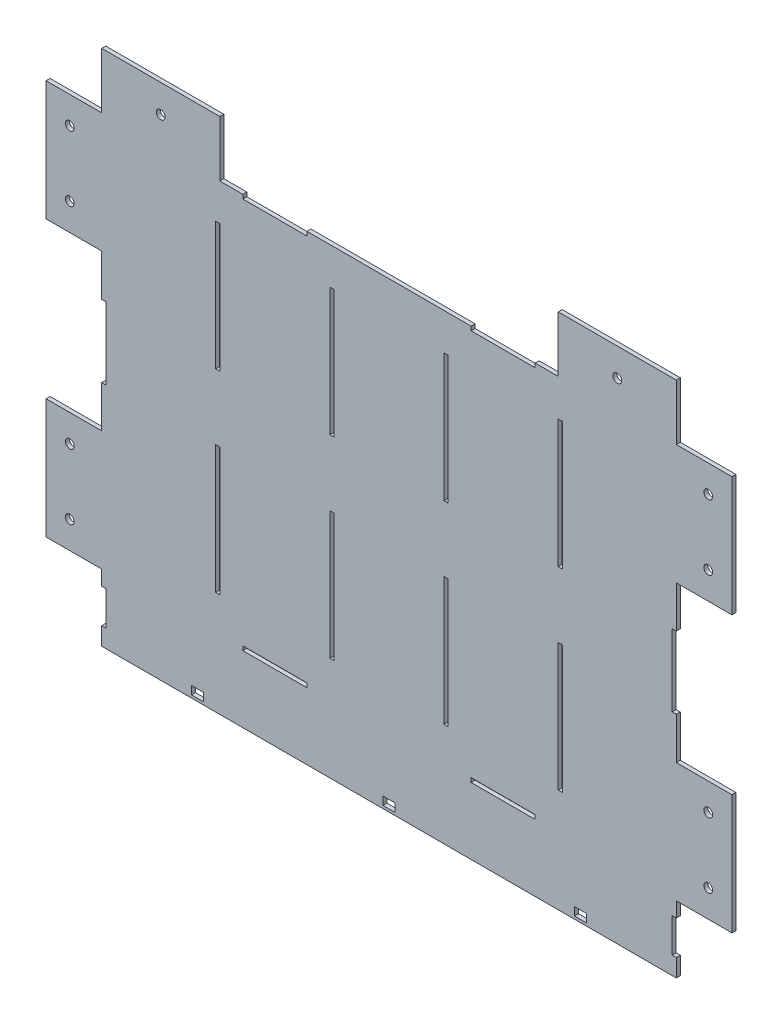
SolidWorks part; units mm, degrees
material "6061-T6 (SS)"
ref_plane "X-Y Datum" through (0, 0, 0) normal (0, 0, 1) x (1, 0, 0)
ref_plane "X-Z Datum" through (0, 0, 0) normal (0, 1, 0) x (1, 0, 0)
ref_plane "Y-Z Datum" through (0, 0, 0) normal (1, 0, 0) x (0, 0, -1)
sketch "Sketch1" plane through (0, 0, 0) normal (0, 0, 1) x (1, 0, 0)
  line L0 (-228.6115, 0) -> (228.6115, 0) construction
  line L1 (-228.6115, -157.216) -> (228.6115, -157.216)
  line L2 (-228.6115, -157.216) -> (-228.6115, 157.216)
  line L3 (-228.6115, 157.216) -> (228.6115, 157.216)
  line L4 (228.6115, -157.216) -> (228.6115, 157.216)
  line L5 (-228.6115, -157.216) -> (228.6115, 157.216) construction
  line L6 (-228.6115, 157.216) -> (228.6115, -157.216) construction
  line L8 (-228.6115, 0) -> (-134.6215, 0) construction
  line L9 (-225.4325, -154.041) -> (-225.4325, 154.041)
  line L10 (-224.4165, -153.025) -> (-138.8165, -153.025) construction
  line L15 (-224.4165, -153.025) -> (-224.4165, 153.025) construction
  line L16 (-224.4165, 153.025) -> (-138.8165, 153.025) construction
  line L17 (-138.8165, -153.025) -> (-138.8165, 153.025) construction
  line L18 (-224.4165, -153.025) -> (-138.8165, 153.025) construction
  line L19 (-224.4165, 153.025) -> (-138.8165, -153.025) construction
  line L20 (-225.4325, 154.041) -> (-137.8005, 154.041)
  line L21 (-137.8005, -154.041) -> (-137.8005, 154.041)
  line L22 (-225.4325, -154.041) -> (-137.8005, -154.041)
  line L26 (-134.6255, 154.041) -> (-46.9935, 154.041)
  line L27 (-133.6095, -153.025) -> (-48.0095, -153.025) construction
  line L28 (-133.6095, -153.025) -> (-133.6095, 153.025) construction
  line L29 (-133.6095, 153.025) -> (-48.0095, 153.025) construction
  line L30 (-48.0095, -153.025) -> (-48.0095, 153.025) construction
  line L31 (-133.6095, -153.025) -> (-48.0095, 153.025) construction
  line L32 (-133.6095, 153.025) -> (-48.0095, -153.025) construction
  line L33 (-46.9935, -154.041) -> (-46.9935, 154.041)
  line L34 (-134.6255, -154.041) -> (-46.9935, -154.041)
  line L35 (-134.6255, -154.041) -> (-134.6255, 154.041)
  line L36 (42.7975, -153.025) -> (42.7975, 153.025) construction
  line L37 (43.8135, -154.041) -> (43.8135, 154.041)
  line L38 (-42.8025, -153.025) -> (42.7975, 153.025) construction
  line L39 (-42.8025, 153.025) -> (42.7975, -153.025) construction
  line L40 (-42.8025, -153.025) -> (-42.8025, 153.025) construction
  line L41 (-43.8185, -154.041) -> (-43.8185, 154.041)
  line L42 (-42.8025, 153.025) -> (42.7975, 153.025) construction
  line L43 (-43.8185, 154.041) -> (43.8135, 154.041)
  line L44 (-42.8025, -153.025) -> (42.7975, -153.025) construction
  line L45 (-43.8185, -154.041) -> (43.8135, -154.041)
  line L46 (133.6045, -153.025) -> (133.6045, 153.025) construction
  line L47 (134.6205, -154.041) -> (134.6205, 154.041)
  line L48 (48.0045, -153.025) -> (133.6045, 153.025) construction
  line L49 (48.0045, 153.025) -> (133.6045, -153.025) construction
  line L50 (48.0045, -153.025) -> (48.0045, 153.025) construction
  line L51 (46.9885, -154.041) -> (46.9885, 154.041)
  line L52 (48.0045, 153.025) -> (133.6045, 153.025) construction
  line L53 (46.9885, 154.041) -> (134.6205, 154.041)
  line L54 (48.0045, -153.025) -> (133.6045, -153.025) construction
  line L55 (46.9885, -154.041) -> (134.6205, -154.041)
  line L56 (224.4115, -153.025) -> (224.4115, 153.025) construction
  line L57 (225.4275, -154.041) -> (225.4275, 154.041)
  line L58 (138.8115, -153.025) -> (224.4115, 153.025) construction
  line L59 (138.8115, 153.025) -> (224.4115, -153.025) construction
  line L60 (138.8115, -153.025) -> (138.8115, 153.025) construction
  line L61 (137.7955, -154.041) -> (137.7955, 154.041)
  line L62 (138.8115, 153.025) -> (224.4115, 153.025) construction
  line L63 (137.7955, 154.041) -> (225.4275, 154.041)
  line L64 (138.8115, -153.025) -> (224.4115, -153.025) construction
  line L65 (137.7955, -154.041) -> (225.4275, -154.041)
  line L67 (-228.6115, -157.216) -> (225.4365, -157.216)
  line L71 (-228.6115, -157.216) -> (228.6115, -157.216)
  line L74 (-225.4365, -157.216) -> (225.4365, -157.216)
  line L75 (-225.4365, -157.216) -> (-225.4365, -208.106)
  line L76 (-225.4365, -208.106) -> (225.4365, -208.106)
  line L77 (225.4365, -157.216) -> (225.4365, -208.106)
  line L79 (-228.6115, -157.216) -> (228.6115, -157.216)
  line L80 (-228.6115, -157.216) -> (-228.6115, -210.392)
  line L81 (-228.6115, -210.392) -> (228.6115, -210.392)
  line L82 (228.6115, -157.216) -> (228.6115, -210.392)
  point P0 (0, 0)
  point P10 (-181.6165, 0)
  point P22 (-90.8095, 0)
  dimension "D1" = 314.432
  dimension "D2" = 457.223
  dimension "D3" = 3.184
  dimension "D4" = 1.016
  dimension "D5" = 3.179
  dimension "D6" = 3.175
  dimension "D7" = 1.016
  dimension "D8" = 90.807
  dimension "D9" = 3.175
  dimension "D11" = 3.175
  dimension "D12" = 50.89
  dimension "D13" = 2.286
  dimension "D14" = 3.175
  dimension "D15" = 3.175
  dimension "D10" = 4
extrude "Boss-Extrude2" add sketch "Sketch1" along normal blind 3.175 contours L61 L65 L57 L63 | L51 L55 L47 L53 | L41 L45 L37 L43 | L35 L34 L33 L26 | L9 L22 L21 L20 | L1 L71 L4 L3 L2 L65 L61 L63 L57 L55 L51 L53 L47 L45 L41 L43 L37 L22 L9 L20 L21 L34 L35 L26 L33 | L77 L71 L75 L76 | L82 L1 L77 L76 L75 L80 L81
sketch "Sketch8" plane through (0, 0, 0) normal (0, 0, -1) x (-1, 0, 0)
  line L0 (-228.6115, -210.392) -> (-228.6115, 157.216) construction
  line L1 (-228.6115, 157.216) -> (-279.4115, 157.216)
  line L2 (-228.6115, 157.216) -> (-228.6115, 61.966)
  line L3 (-228.6115, 61.966) -> (-279.4115, 61.966)
  line L4 (-279.4115, 157.216) -> (-279.4115, 61.966)
  line L5 (-228.6115, -157.216) -> (-279.4115, -157.216)
  line L6 (-228.6115, -157.216) -> (-228.6115, -61.966)
  line L7 (-228.6115, -61.966) -> (-279.4115, -61.966)
  line L8 (-279.4115, -157.216) -> (-279.4115, -61.966)
  line L9 (-254.0115, 83.591) -> (-254.0115, 135.591)
  line L10 (-254.0115, -83.591) -> (-254.0115, -135.591) construction
  line L11 (-279.4115, 109.591) -> (-228.6115, 109.591) construction
  line L13 (-272.8865, 157.216) -> (-272.8865, 61.966)
  line L15 (-228.6115, -109.591) -> (-279.4115, -109.591) construction
  line L16 (-181.6215, 201.666) -> (-181.6215, 157.216) construction
  line L17 (-228.6115, 157.216) -> (-134.6315, 157.216)
  line L18 (-228.6115, 157.216) -> (-228.6115, 201.666)
  line L19 (-228.6115, 201.666) -> (-134.6315, 201.666)
  line L20 (-134.6315, 157.216) -> (-134.6315, 201.666)
  line L22 (228.6115, 157.216) -> (-228.6115, 157.216) construction
  line L23 (-272.8865, -61.966) -> (-272.8865, -157.216)
  circle A3 centre (-254.0115, -83.591) radius 3
  circle A4 centre (-254.0115, -135.591) radius 3
  circle A5 centre (-181.6215, 179.441) radius 3
  circle A6 centre (-254.0115, 135.591) radius 3
  circle A7 centre (-254.0115, 83.591) radius 3
  point P13 (-254.0115, -109.591)
  point P19 (-254.0115, 109.591)
  point P21 (-257.0115, 135.591)
  point P45 (-254.0115, -138.591)
  point P46 (-254.0115, -157.216)
  dimension "D1" = 95.25
  dimension "D2" = 52
  dimension "D4" = 52
  dimension "D5" = 6
  dimension "D7" = 93.98
  dimension "D8" = 123.932
  dimension "D9" = 25.4
  dimension "D3" = 6
  dimension "D11" = 6
  dimension "D6" = 22.225
  dimension "D10" = 15.875
extrude "Boss-Extrude3" add sketch "Sketch8" against normal blind 3.175
mirror "Mirror7" about plane through (0, 0, 0) normal (1, 0, 0) of "Boss-Extrude3"
hole_wizard "M6 Clearance Hole1" positions "Sketch11" profile "Sketch10" hole size "M6" standard "ANSI Metric" end condition through all
sketch "Sketch11" plane through (0, 0, 0) normal (0, 0, -1) x (-1, 0, 0)
  point P0 (-254.0115, -135.591)
  point P3 (-254.0115, -83.591)
  point P6 (-254.0115, 83.591)
  point P9 (-254.0115, 135.591)
  point P12 (-181.6215, 179.441)
sketch "Sketch10" plane through (254.0115, -135.591, 0) normal (1, 0, 0) x (0, 1, 0)
  line L0 (0, 0) -> (0, 3.175)
  line L1 (0, 3.175) -> (3.5, 3.175)
  line L2 (3.5, 3.175) -> (3.5, 0)
  line L5 (3.5, 0) -> (0, 0)
  line L11 (0, -6.35) -> (0, 107.95) construction
  dimension "Thru Hole Dia." = 7
  dimension "Thru Hole Depth" = 3.175
mirror "Mirror8" about plane through (0, 0, 0) normal (1, 0, 0) of "M6 Clearance Hole1"
sketch "Sketch12" plane through (0, 0, 0) normal (0, 0, -1) x (-1, 0, 0)
  line L0 (228.6115, -157.216) -> (-228.6115, -157.216) construction
  line L1 (228.6115, -157.216) -> (228.6115, 157.216) construction
  line L2 (228.6115, 157.216) -> (-228.6115, 157.216) construction
  line L3 (-228.6115, -157.216) -> (-228.6115, 157.216) construction
  line L4 (228.6115, -157.216) -> (-228.6115, -157.216) construction
  line L5 (228.6115, -157.216) -> (-228.6115, -157.216) construction
  line L6 (228.6115, -157.216) -> (228.6115, -210.392) construction
  line L7 (228.6115, -210.392) -> (-228.6115, -210.392) construction
  line L8 (-228.6115, -157.216) -> (-228.6115, -210.392) construction
  line L9 (228.6115, -157.216) -> (-225.4365, -157.216) construction
  line L10 (225.4325, -154.041) -> (225.4325, 154.041) construction
  line L11 (225.4325, 154.041) -> (137.8005, 154.041) construction
  line L12 (137.8005, -154.041) -> (137.8005, 154.041) construction
  line L13 (225.4325, -154.041) -> (137.8005, -154.041) construction
  line L14 (-43.8135, -154.041) -> (-43.8135, 154.041) construction
  line L15 (43.8185, 154.041) -> (-43.8135, 154.041) construction
  line L16 (43.8185, -154.041) -> (43.8185, 154.041) construction
  line L17 (43.8185, -154.041) -> (-43.8135, -154.041) construction
  line L18 (134.6255, -154.041) -> (46.9935, -154.041) construction
  line L19 (46.9935, -154.041) -> (46.9935, 154.041) construction
  line L20 (134.6255, 154.041) -> (46.9935, 154.041) construction
  line L21 (134.6255, -154.041) -> (134.6255, 154.041) construction
  line L22 (225.4365, -157.216) -> (-225.4365, -157.216) construction
  line L23 (225.4365, -157.216) -> (225.4365, -208.106) construction
  line L24 (225.4365, -208.106) -> (-225.4365, -208.106) construction
  line L25 (-225.4365, -157.216) -> (-225.4365, -208.106) construction
  line L26 (-225.4275, -154.041) -> (-225.4275, 154.041) construction
  line L27 (-137.7955, 154.041) -> (-225.4275, 154.041) construction
  line L28 (-137.7955, -154.041) -> (-137.7955, 154.041) construction
  line L29 (-137.7955, -154.041) -> (-225.4275, -154.041) construction
  line L30 (-134.6205, -154.041) -> (-134.6205, 154.041) construction
  line L31 (-46.9885, 154.041) -> (-134.6205, 154.041) construction
  line L32 (-46.9885, -154.041) -> (-46.9885, 154.041) construction
  line L33 (-46.9885, -154.041) -> (-134.6205, -154.041) construction
  line L34 (228.6115, -157.216) -> (-228.6115, -157.216) construction
  line L35 (228.6115, -157.216) -> (228.6115, 157.216) construction
  line L36 (228.6115, 157.216) -> (-228.6115, 157.216) construction
  line L37 (-228.6115, -157.216) -> (-228.6115, 157.216) construction
  line L38 (228.6115, -157.216) -> (-228.6115, -157.216) construction
  line L39 (228.6115, -157.216) -> (-228.6115, -157.216) construction
  line L40 (228.6115, -157.216) -> (228.6115, -210.392) construction
  line L41 (228.6115, -210.392) -> (-228.6115, -210.392)
  line L42 (-228.6115, -157.216) -> (-228.6115, -210.392)
  line L43 (228.6115, -157.216) -> (-225.4365, -157.216) construction
  line L44 (225.4325, -154.041) -> (225.4325, 154.041) construction
  line L45 (225.4325, 154.041) -> (137.8005, 154.041) construction
  line L46 (137.8005, -154.041) -> (137.8005, 154.041) construction
  line L47 (225.4325, -154.041) -> (137.8005, -154.041) construction
  line L48 (-43.8135, -154.041) -> (-43.8135, 154.041) construction
  line L49 (43.8185, 154.041) -> (-43.8135, 154.041) construction
  line L50 (43.8185, -154.041) -> (43.8185, 154.041) construction
  line L51 (43.8185, -154.041) -> (-43.8135, -154.041) construction
  line L52 (134.6255, -154.041) -> (46.9935, -154.041) construction
  line L53 (46.9935, -154.041) -> (46.9935, 154.041) construction
  line L54 (134.6255, 154.041) -> (46.9935, 154.041) construction
  line L55 (134.6255, -154.041) -> (134.6255, 154.041) construction
  line L56 (225.4365, -157.216) -> (-225.4365, -157.216) construction
  line L57 (225.4365, -157.216) -> (225.4365, -208.106) construction
  line L58 (225.4365, -208.106) -> (-225.4365, -208.106) construction
  line L59 (-225.4365, -157.216) -> (-225.4365, -208.106) construction
  line L60 (-225.4275, -154.041) -> (-225.4275, 154.041) construction
  line L61 (-137.7955, 154.041) -> (-225.4275, 154.041) construction
  line L62 (-137.7955, -154.041) -> (-137.7955, 154.041) construction
  line L63 (-137.7955, -154.041) -> (-225.4275, -154.041) construction
  line L64 (-134.6205, -154.041) -> (-134.6205, 154.041) construction
  line L65 (-46.9885, 154.041) -> (-134.6205, 154.041) construction
  line L66 (-46.9885, -154.041) -> (-46.9885, 154.041) construction
  line L67 (-46.9885, -154.041) -> (-134.6205, -154.041) construction
  line L68 (-228.6115, 0) -> (-225.4275, 0) construction
  line L69 (-90.8045, 154.041) -> (-90.8045, 157.216) construction
  line L70 (-90.8045, -154.041) -> (-90.8045, -157.216) construction
  line L71 (225.4325, 0) -> (228.6115, 0) construction
  line L72 (90.8095, -154.041) -> (90.8095, -157.216) construction
  line L73 (90.8095, 154.041) -> (90.8095, 157.216) construction
  line L74 (134.6255, 0) -> (137.8005, 0)
  line L75 (43.8185, 0) -> (46.9935, 0)
  line L76 (-46.9885, 0) -> (-43.8135, 0)
  line L77 (-137.7955, 0) -> (-134.6205, 0)
  line L78 (-225.4365, -182.661) -> (-228.6115, -182.661) construction
  line L79 (-228.6115, 28.575) -> (-225.4275, 28.575)
  line L80 (-228.6115, 28.575) -> (-228.6115, -28.575)
  line L81 (-228.6115, -28.575) -> (-225.4275, -28.575)
  line L82 (-225.4275, 28.575) -> (-225.4275, -28.575)
  line L83 (-228.6115, 28.575) -> (-225.4275, -28.575) construction
  line L84 (-228.6115, -28.575) -> (-225.4275, 28.575) construction
  line L85 (225.4325, 28.575) -> (228.6115, 28.575)
  line L86 (225.4325, 28.575) -> (225.4325, -28.575)
  line L87 (225.4325, -28.575) -> (228.6115, -28.575)
  line L88 (228.6115, 28.575) -> (228.6115, -28.575)
  line L89 (225.4325, 28.575) -> (228.6115, -28.575) construction
  line L90 (225.4325, -28.575) -> (228.6115, 28.575) construction
  line L91 (-116.2045, 157.216) -> (-65.4045, 157.216)
  line L92 (-116.2045, 157.216) -> (-116.2045, 154.041)
  line L93 (-116.2045, 154.041) -> (-65.4045, 154.041)
  line L94 (-65.4045, 157.216) -> (-65.4045, 154.041)
  line L95 (-116.2045, 157.216) -> (-65.4045, 154.041) construction
  line L96 (-116.2045, 154.041) -> (-65.4045, 157.216) construction
  line L97 (65.4095, 157.216) -> (116.2095, 157.216)
  line L98 (65.4095, 157.216) -> (65.4095, 154.041)
  line L99 (65.4095, 154.041) -> (116.2095, 154.041)
  line L100 (116.2095, 157.216) -> (116.2095, 154.041)
  line L101 (65.4095, 157.216) -> (116.2095, 154.041) construction
  line L102 (65.4095, 154.041) -> (116.2095, 157.216) construction
  line L103 (-116.2045, -154.041) -> (-65.4045, -154.041)
  line L104 (-116.2045, -154.041) -> (-116.2045, -157.216)
  line L105 (-116.2045, -157.216) -> (-65.4045, -157.216)
  line L106 (-65.4045, -154.041) -> (-65.4045, -157.216)
  line L107 (-116.2045, -154.041) -> (-65.4045, -157.216) construction
  line L108 (-116.2045, -157.216) -> (-65.4045, -154.041) construction
  line L109 (65.4095, -154.041) -> (116.2095, -154.041)
  line L110 (65.4095, -154.041) -> (65.4095, -157.216)
  line L111 (65.4095, -157.216) -> (116.2095, -157.216)
  line L112 (116.2095, -154.041) -> (116.2095, -157.216)
  line L113 (65.4095, -154.041) -> (116.2095, -157.216) construction
  line L114 (65.4095, -157.216) -> (116.2095, -154.041) construction
  line L115 (225.4365, -182.661) -> (228.6115, -182.661) construction
  line L116 (-136.208, 0) -> (-136.208, 154.041) construction
  line L117 (-228.6115, -169.1673) -> (-225.4365, -169.1673)
  line L118 (-228.6115, -169.1673) -> (-228.6115, -196.1548)
  line L119 (-228.6115, -196.1548) -> (-225.4365, -196.1548)
  line L120 (-225.4365, -169.1673) -> (-225.4365, -196.1548)
  line L121 (-228.6115, -169.1673) -> (-225.4365, -196.1548) construction
  line L122 (-228.6115, -196.1548) -> (-225.4365, -169.1673) construction
  line L123 (225.4365, -169.1673) -> (228.6115, -169.1673)
  line L124 (225.4365, -169.1673) -> (225.4365, -196.1548)
  line L125 (225.4365, -196.1548) -> (228.6115, -196.1548)
  line L126 (228.6115, -169.1673) -> (228.6115, -196.1548)
  line L127 (225.4365, -169.1673) -> (228.6115, -196.1548) construction
  line L128 (225.4365, -196.1548) -> (228.6115, -169.1673) construction
  line L129 (-136.208, 0) -> (-136.208, -154.041) construction
  line L130 (-228.6877, 28.6512) -> (-225.3513, 28.6512)
  line L131 (-137.7955, 127.8205) -> (-134.6205, 127.8205)
  line L132 (-137.7955, 127.8205) -> (-137.7955, 26.2205)
  line L133 (-137.7955, 26.2205) -> (-134.6205, 26.2205)
  line L134 (-134.6205, 127.8205) -> (-134.6205, 26.2205)
  line L135 (-137.7955, 127.8205) -> (-134.6205, 26.2205) construction
  line L136 (-137.7955, 26.2205) -> (-134.6205, 127.8205) construction
  line L137 (-137.7955, -26.2205) -> (-134.6205, -26.2205)
  line L138 (-137.7955, -26.2205) -> (-137.7955, -127.8205)
  line L139 (-137.7955, -127.8205) -> (-134.6205, -127.8205)
  line L140 (-134.6205, -26.2205) -> (-134.6205, -127.8205)
  line L141 (-137.7955, -26.2205) -> (-134.6205, -127.8205) construction
  line L142 (-137.7955, -127.8205) -> (-134.6205, -26.2205) construction
  line L143 (-225.3513, 28.6512) -> (-225.3513, -28.6512)
  line L144 (-228.6877, -28.6512) -> (-225.3513, -28.6512)
  line L145 (-228.6877, 28.6512) -> (-228.6877, -28.6512)
  line L146 (-225.3603, -169.0911) -> (-225.3603, -196.231)
  line L147 (-228.6877, -196.231) -> (-225.3603, -196.231)
  line L148 (-228.6877, -169.0911) -> (-228.6877, -196.231)
  line L149 (-228.6877, -169.0911) -> (-225.3603, -169.0911)
  line L150 (-116.2807, -153.9648) -> (-116.2807, -157.2922)
  line L151 (-116.2807, -157.2922) -> (-65.3283, -157.2922)
  line L152 (-65.3283, -153.9648) -> (-65.3283, -157.2922)
  line L153 (-116.2807, -153.9648) -> (-65.3283, -153.9648)
  line L154 (65.3333, -153.9648) -> (65.3333, -157.2922)
  line L155 (65.3333, -157.2922) -> (116.2857, -157.2922)
  line L156 (116.2857, -153.9648) -> (116.2857, -157.2922)
  line L157 (65.3333, -153.9648) -> (116.2857, -153.9648)
  line L158 (225.3603, -169.0911) -> (228.6877, -169.0911)
  line L159 (228.6877, -169.0911) -> (228.6877, -196.231)
  line L160 (225.3603, -196.231) -> (228.6877, -196.231)
  line L161 (225.3603, -169.0911) -> (225.3603, -196.231)
  line L162 (-116.2807, 157.2922) -> (-116.2807, 153.9648)
  line L163 (-116.2807, 153.9648) -> (-65.3283, 153.9648)
  line L164 (-65.3283, 157.2922) -> (-65.3283, 153.9648)
  line L165 (-116.2807, 157.2922) -> (-65.3283, 157.2922)
  line L166 (65.3333, 157.2922) -> (65.3333, 153.9648)
  line L167 (65.3333, 153.9648) -> (116.2857, 153.9648)
  line L168 (116.2857, 157.2922) -> (116.2857, 153.9648)
  line L169 (65.3333, 157.2922) -> (116.2857, 157.2922)
  line L170 (225.3563, 28.6512) -> (228.6877, 28.6512)
  line L171 (228.6877, 28.6512) -> (228.6877, -28.6512)
  line L172 (225.3563, -28.6512) -> (228.6877, -28.6512)
  line L173 (225.3563, 28.6512) -> (225.3563, -28.6512)
  point P50 (-227.0195, 0)
  point P55 (227.022, 0)
  point P60 (-90.8045, 155.6285)
  point P65 (90.8095, 155.6285)
  point P70 (-90.8045, -155.6285)
  point P75 (90.8095, -155.6285)
  point P84 (-227.024, -182.661)
  point P89 (227.024, -182.661)
  point P96 (-136.208, -77.0205)
  point P98 (-136.208, 77.0205)
  line M27 (228.6115, -210.392) -> (228.6115, -157.216)
  line M31 (228.6115, -61.966) -> (228.6115, 61.966)
  line M38 (134.6315, 157.216) -> (-134.6315, 157.216)
  line M45 (-228.6115, 61.966) -> (-228.6115, -61.966)
  line M49 (-228.6115, -157.216) -> (-228.6115, -210.392)
  dimension "D1" = 57.15
  dimension "D2" = 50.8
  dimension "D3" = 26.9875
  dimension "D4" = 101.6
  dimension "D5" = 0.0762
  dimension "D6" = 0.0762
extrude "Cut-Extrude3" cut sketch "Sketch12" against normal through all contours L82 L79 L81 M45 | L144 L143 L130 L79 L82 L81 M45 | L120 L117 L42 L119 | L149 L42 L117 L120 L119 L147 L146 M49 | L106 L103 L104 L105 | L153 L150 L151 L152 L103 L106 L105 L104 | L112 L109 L110 L111 | L157 L154 L155 L156 L109 L112 L111 L110 | L124 L125 L123 M27 | L158 L161 L160 L125 L124 L123 M27 | L86 L87 L85 M31 | L170 L173 L172 L87 L86 L85 M31 | L100 L98 L99 M38 | L168 L100 L99 L98 L166 L167 M38 | L94 L92 L93 M38 | L164 L94 L93 L92 L162 L163 M38
sketch "Sketch14" plane through (0, 0, 0) normal (0, 0, -1) x (-1, 0, 0)
  line L0 (228.6115, -210.392) -> (-228.6115, -210.392) construction
  line L1 (-228.6115, -157.216) -> (-228.6115, -210.392) construction
  line L2 (-137.7955, 0) -> (-134.6205, 0) construction
  line L3 (-46.9885, 0) -> (-43.8135, 0) construction
  line L4 (228.6115, 28.575) -> (225.4325, 28.575)
  line L5 (228.6115, -28.575) -> (228.6115, 28.575)
  line L6 (225.4325, -28.575) -> (228.6115, -28.575)
  line L7 (225.4325, 28.575) -> (225.4325, -28.575)
  line L8 (228.6115, 28.575) -> (225.4325, 28.575)
  line L9 (228.6115, -28.575) -> (228.6115, 28.575)
  line L10 (225.4325, -28.575) -> (228.6115, -28.575)
  line L11 (225.4325, 28.575) -> (225.4325, -28.575)
  line L12 (-225.4275, 28.575) -> (-228.6115, 28.575)
  line L13 (-225.4275, -28.575) -> (-225.4275, 28.575)
  line L14 (-228.6115, -28.575) -> (-225.4275, -28.575)
  line L15 (-228.6115, 28.575) -> (-228.6115, -28.575)
  line L16 (-225.4275, 28.575) -> (-228.6115, 28.575)
  line L17 (-225.4275, -28.575) -> (-225.4275, 28.575)
  line L18 (-228.6115, -28.575) -> (-225.4275, -28.575)
  line L19 (-228.6115, 28.575) -> (-228.6115, -28.575)
  line L20 (116.2095, -154.041) -> (65.4095, -154.041)
  line L21 (116.2095, -157.216) -> (116.2095, -154.041)
  line L22 (65.4095, -157.216) -> (116.2095, -157.216)
  line L23 (65.4095, -154.041) -> (65.4095, -157.216)
  line L24 (116.2095, -154.041) -> (65.4095, -154.041)
  line L25 (116.2095, -157.216) -> (116.2095, -154.041)
  line L26 (65.4095, -157.216) -> (116.2095, -157.216)
  line L27 (65.4095, -154.041) -> (65.4095, -157.216)
  line L28 (-65.4045, -154.041) -> (-116.2045, -154.041)
  line L29 (-65.4045, -157.216) -> (-65.4045, -154.041)
  line L30 (-116.2045, -157.216) -> (-65.4045, -157.216)
  line L31 (-116.2045, -154.041) -> (-116.2045, -157.216)
  line L32 (-65.4045, -154.041) -> (-116.2045, -154.041)
  line L33 (-65.4045, -157.216) -> (-65.4045, -154.041)
  line L34 (-116.2045, -157.216) -> (-65.4045, -157.216)
  line L35 (-116.2045, -154.041) -> (-116.2045, -157.216)
  line L36 (116.2095, 157.216) -> (65.4095, 157.216)
  line L37 (116.2095, 154.041) -> (116.2095, 157.216)
  line L38 (65.4095, 154.041) -> (116.2095, 154.041)
  line L39 (65.4095, 157.216) -> (65.4095, 154.041)
  line L40 (116.2095, 157.216) -> (65.4095, 157.216)
  line L41 (116.2095, 154.041) -> (116.2095, 157.216)
  line L42 (65.4095, 154.041) -> (116.2095, 154.041)
  line L43 (65.4095, 157.216) -> (65.4095, 154.041)
  line L44 (-65.4045, 157.216) -> (-116.2045, 157.216)
  line L45 (-116.2045, 157.216) -> (-116.2045, 154.041)
  line L46 (-116.2045, 154.041) -> (-65.4045, 154.041)
  line L47 (-65.4045, 154.041) -> (-65.4045, 157.216)
  line L48 (-65.4045, 157.216) -> (-116.2045, 157.216)
  line L49 (-116.2045, 157.216) -> (-116.2045, 154.041)
  line L50 (-116.2045, 154.041) -> (-65.4045, 154.041)
  line L51 (-65.4045, 154.041) -> (-65.4045, 157.216)
  line L52 (228.6115, -169.1673) -> (225.4365, -169.1673)
  line L53 (228.6115, -196.1548) -> (228.6115, -169.1673)
  line L54 (225.4365, -196.1548) -> (228.6115, -196.1548)
  line L55 (225.4365, -169.1673) -> (225.4365, -196.1548)
  line L56 (228.6115, -169.1673) -> (225.4365, -169.1673)
  line L57 (228.6115, -196.1548) -> (228.6115, -169.1673)
  line L58 (225.4365, -196.1548) -> (228.6115, -196.1548)
  line L59 (225.4365, -169.1673) -> (225.4365, -196.1548)
  line L60 (-225.4365, -169.1673) -> (-228.6115, -169.1673)
  line L61 (-225.4365, -196.1548) -> (-225.4365, -169.1673)
  line L62 (-228.6115, -196.1548) -> (-225.4365, -196.1548)
  line L63 (-228.6115, -169.1673) -> (-228.6115, -196.1548)
  line L64 (-225.4365, -169.1673) -> (-228.6115, -169.1673)
  line L65 (-225.4365, -196.1548) -> (-225.4365, -169.1673)
  line L66 (-228.6115, -196.1548) -> (-225.4365, -196.1548)
  line L67 (-228.6115, -169.1673) -> (-228.6115, -196.1548)
  line L68 (-134.6205, -26.2205) -> (-137.7955, -26.2205)
  line L69 (-134.6205, -127.8205) -> (-134.6205, -26.2205)
  line L70 (-137.7955, -127.8205) -> (-134.6205, -127.8205)
  line L71 (-137.7955, -26.2205) -> (-137.7955, -127.8205)
  line L72 (-134.6205, -26.2205) -> (-137.7955, -26.2205)
  line L73 (-134.6205, -127.8205) -> (-134.6205, -26.2205)
  line L74 (-137.7955, -127.8205) -> (-134.6205, -127.8205)
  line L75 (-137.7955, -26.2205) -> (-137.7955, -127.8205)
  line L76 (-134.6205, 127.8205) -> (-137.7955, 127.8205)
  line L77 (-134.6205, 26.2205) -> (-134.6205, 127.8205)
  line L78 (-137.7955, 26.2205) -> (-134.6205, 26.2205)
  line L79 (-137.7955, 127.8205) -> (-137.7955, 26.2205)
  line L80 (-134.6205, 127.8205) -> (-137.7955, 127.8205)
  line L81 (-134.6205, 26.2205) -> (-134.6205, 127.8205)
  line L82 (-137.7955, 26.2205) -> (-134.6205, 26.2205)
  line L83 (-137.7955, 127.8205) -> (-137.7955, 26.2205)
  line L84 (65.3333, -153.9648) -> (65.3333, -157.2922)
  line L85 (65.3333, -157.2922) -> (116.2857, -157.2922)
  line L86 (116.2857, -157.2922) -> (116.2857, -153.9648)
  line L87 (116.2857, -153.9648) -> (65.3333, -153.9648)
  line L88 (65.3333, -153.9648) -> (65.3333, -157.2922)
  line L89 (65.3333, -157.2922) -> (116.2857, -157.2922)
  line L90 (116.2857, -157.2922) -> (116.2857, -153.9648)
  line L91 (116.2857, -153.9648) -> (65.3333, -153.9648)
  line L92 (-116.2807, -153.9648) -> (-116.2807, -157.2922)
  line L93 (-116.2807, -157.2922) -> (-65.3283, -157.2922)
  line L94 (-65.3283, -157.2922) -> (-65.3283, -153.9648)
  line L95 (-65.3283, -153.9648) -> (-116.2807, -153.9648)
  line L96 (-116.2807, -153.9648) -> (-116.2807, -157.2922)
  line L97 (-116.2807, -157.2922) -> (-65.3283, -157.2922)
  line L98 (-65.3283, -157.2922) -> (-65.3283, -153.9648)
  line L99 (-65.3283, -153.9648) -> (-116.2807, -153.9648)
  line L100 (-225.3603, -196.231) -> (-225.3603, -169.0911)
  line L101 (-228.6877, -196.231) -> (-225.3603, -196.231)
  line L102 (-228.6877, -169.0911) -> (-228.6877, -196.231)
  line L103 (-225.3603, -169.0911) -> (-228.6877, -169.0911)
  line L104 (-225.3603, -196.231) -> (-225.3603, -169.0911)
  line L105 (-228.6877, -196.231) -> (-225.3603, -196.231)
  line L106 (-228.6877, -169.0911) -> (-228.6877, -196.231)
  line L107 (-225.3603, -169.0911) -> (-228.6877, -169.0911)
  line L108 (-228.6877, -28.6512) -> (-225.3513, -28.6512)
  line L109 (-228.6877, 28.6512) -> (-228.6877, -28.6512)
  line L110 (-225.3513, 28.6512) -> (-228.6877, 28.6512)
  line L111 (-225.3513, -28.6512) -> (-225.3513, 28.6512)
  line L112 (-228.6877, -28.6512) -> (-225.3513, -28.6512)
  line L113 (-228.6877, 28.6512) -> (-228.6877, -28.6512)
  line L114 (-225.3513, 28.6512) -> (-228.6877, 28.6512)
  line L115 (-225.3513, -28.6512) -> (-225.3513, 28.6512)
  line L116 (228.6877, 28.6512) -> (225.3563, 28.6512)
  line L117 (228.6877, -28.6512) -> (228.6877, 28.6512)
  line L118 (225.3563, -28.6512) -> (228.6877, -28.6512)
  line L119 (225.3563, 28.6512) -> (225.3563, -28.6512)
  line L120 (228.6877, 28.6512) -> (225.3563, 28.6512)
  line L121 (228.6877, -28.6512) -> (228.6877, 28.6512)
  line L122 (225.3563, -28.6512) -> (228.6877, -28.6512)
  line L123 (225.3563, 28.6512) -> (225.3563, -28.6512)
  line L124 (65.3333, 157.2922) -> (65.3333, 153.9648)
  line L125 (65.3333, 153.9648) -> (116.2857, 153.9648)
  line L126 (116.2857, 153.9648) -> (116.2857, 157.2922)
  line L127 (116.2857, 157.2922) -> (65.3333, 157.2922)
  line L128 (65.3333, 157.2922) -> (65.3333, 153.9648)
  line L129 (65.3333, 153.9648) -> (116.2857, 153.9648)
  line L130 (116.2857, 153.9648) -> (116.2857, 157.2922)
  line L131 (116.2857, 157.2922) -> (65.3333, 157.2922)
  line L132 (-116.2807, 157.2922) -> (-116.2807, 153.9648)
  line L133 (-116.2807, 153.9648) -> (-65.3283, 153.9648)
  line L134 (-65.3283, 153.9648) -> (-65.3283, 157.2922)
  line L135 (-65.3283, 157.2922) -> (-116.2807, 157.2922)
  line L136 (-116.2807, 157.2922) -> (-116.2807, 153.9648)
  line L137 (-116.2807, 153.9648) -> (-65.3283, 153.9648)
  line L138 (-65.3283, 153.9648) -> (-65.3283, 157.2922)
  line L139 (-65.3283, 157.2922) -> (-116.2807, 157.2922)
  line L140 (225.3603, -196.231) -> (228.6877, -196.231)
  line L141 (225.3603, -169.0911) -> (225.3603, -196.231)
  line L142 (228.6877, -169.0911) -> (225.3603, -169.0911)
  line L143 (228.6877, -196.231) -> (228.6877, -169.0911)
  line L144 (225.3603, -196.231) -> (228.6877, -196.231)
  line L145 (225.3603, -169.0911) -> (225.3603, -196.231)
  line L146 (228.6877, -169.0911) -> (225.3603, -169.0911)
  line L147 (228.6877, -196.231) -> (228.6877, -169.0911)
  line L148 (43.8185, 0) -> (46.9935, 0) construction
  line L149 (134.6255, 0) -> (137.8005, 0) construction
  line L150 (228.6115, -210.392) -> (-228.6115, -210.392)
  line L151 (-228.6115, -157.216) -> (-228.6115, -210.392)
  line L152 (-137.7955, 0) -> (-134.6205, 0)
  line L153 (-46.9885, 0) -> (-43.8135, 0)
  line L154 (43.8185, 0) -> (46.9935, 0)
  line L155 (134.6255, 0) -> (137.8005, 0)
  line L156 (-134.5443, -26.1443) -> (-137.8717, -26.1443)
  line L157 (-137.8717, -26.1443) -> (-137.8717, -127.8967)
  line L158 (-137.8717, -127.8967) -> (-134.5443, -127.8967)
  line L159 (-134.5443, -127.8967) -> (-134.5443, -26.1443)
  line L160 (-137.8717, 26.1443) -> (-134.5443, 26.1443)
  line L161 (-134.5443, 26.1443) -> (-134.5443, 127.8967)
  line L162 (-134.5443, 127.8967) -> (-137.8717, 127.8967)
  line L163 (-137.8717, 127.8967) -> (-137.8717, 26.1443)
  dimension "D1" = 0
  dimension "D2" = 0
  dimension "D3" = 0
  dimension "D4" = 0
  dimension "D5" = 0
  dimension "D6" = 0
  dimension "D7" = 0
  dimension "D8" = 0
  dimension "D9" = 0
  dimension "D10" = 0
  dimension "D11" = 0
  dimension "D12" = 0
  dimension "D13" = 0
  dimension "D14" = 0
  dimension "D15" = 0
  dimension "D16" = 0
  dimension "D17" = 0
  dimension "D18" = 0
  dimension "D19" = 0.0762
extrude "Cut-Extrude4" cut sketch "Sketch14" against normal through all contours L80 L83 L82 L81 | L162 L163 L160 L161 L83 L80 L81 L82 | L72 L75 L74 L73 | L158 L159 L156 L157 L75 L72 L73 L74
pattern_linear "LPattern2" count 4 spacing 90.807 along (-1, 0, 0) of "Cut-Extrude4"
sketch "Sketch16" plane through (0, 0, 3.175) normal (0, 0, 1) x (1, 0, 0)
  line L0 (-147.6375, -201.7547) -> (-147.6375, -208.1047) construction
  line L1 (-147.6375, -201.7547) -> (-157.1625, -201.7547) construction
  line L2 (-147.6375, -208.1047) -> (-157.1625, -208.1047) construction
  line L3 (-157.1625, -201.7547) -> (-157.1625, -208.1047) construction
  line L4 (-147.6375, -201.7547) -> (-147.6375, -208.1047)
  line L5 (-147.6375, -201.7547) -> (-157.1625, -201.7547)
  line L6 (-147.6375, -208.1047) -> (-157.1625, -208.1047)
  line L7 (-157.1625, -201.7547) -> (-157.1625, -208.1047)
  line L8 (4.7625, -201.7547) -> (4.7625, -208.1047) construction
  line L9 (4.7625, -208.1047) -> (-4.7625, -208.1047) construction
  line L10 (4.7625, -201.7547) -> (-4.7625, -201.7547) construction
  line L11 (-4.7625, -201.7547) -> (-4.7625, -208.1047) construction
  line L12 (4.7625, -201.7547) -> (4.7625, -208.1047)
  line L13 (4.7625, -208.1047) -> (-4.7625, -208.1047)
  line L14 (4.7625, -201.7547) -> (-4.7625, -201.7547)
  line L15 (-4.7625, -201.7547) -> (-4.7625, -208.1047)
  line L16 (157.1625, -201.7547) -> (157.1625, -208.1047) construction
  line L17 (157.1625, -201.7547) -> (147.6375, -201.7547) construction
  line L18 (157.1625, -208.1047) -> (147.6375, -208.1047) construction
  line L19 (147.6375, -201.7547) -> (147.6375, -208.1047) construction
  line L20 (157.1625, -201.7547) -> (157.1625, -208.1047)
  line L21 (157.1625, -201.7547) -> (147.6375, -201.7547)
  line L22 (157.1625, -208.1047) -> (147.6375, -208.1047)
  line L23 (147.6375, -201.7547) -> (147.6375, -208.1047)
  line L24 (-157.2387, -201.6785) -> (-157.2387, -208.1809)
  line L25 (-147.5613, -208.1809) -> (-157.2387, -208.1809)
  line L26 (-147.5613, -201.6785) -> (-147.5613, -208.1809)
  line L27 (-147.5613, -201.6785) -> (-157.2387, -201.6785)
  line L28 (4.8387, -201.6785) -> (-4.8387, -201.6785)
  line L29 (-4.8387, -201.6785) -> (-4.8387, -208.1809)
  line L30 (4.8387, -208.1809) -> (-4.8387, -208.1809)
  line L31 (4.8387, -201.6785) -> (4.8387, -208.1809)
  line L32 (157.2387, -201.6785) -> (147.5613, -201.6785)
  line L33 (147.5613, -201.6785) -> (147.5613, -208.1809)
  line L34 (157.2387, -208.1809) -> (147.5613, -208.1809)
  line L35 (157.2387, -201.6785) -> (157.2387, -208.1809)
  dimension "D1" = 0.0762
extrude "Cut-Extrude5" cut sketch "Sketch16" against normal through all contours L21 L23 L22 L20 | L35 L32 L33 L34 L23 L21 L20 L22 | L14 L15 L13 L12 | L31 L28 L29 L30 L15 L14 L12 L13 | L5 L7 L6 L4 | L26 L27 L24 L25 L7 L5 L4 L6
